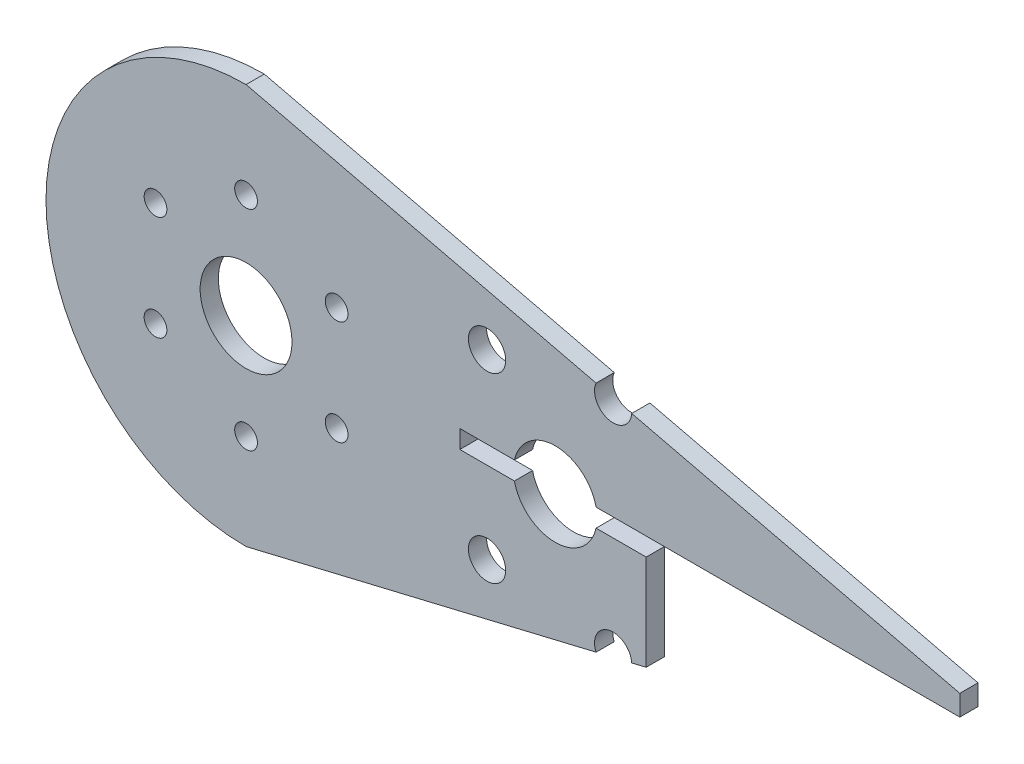
SolidWorks part; units mm, degrees
ref_plane "前视基准面" through (0, 0, 0) normal (0, 0, 1) x (1, 0, 0)
ref_plane "上视基准面" through (0, 0, 0) normal (0, 1, 0) x (1, 0, 0)
ref_plane "右视基准面" through (0, 0, 0) normal (1, 0, 0) x (0, 0, -1)
sketch "草图1" plane through (0, 0, 0) normal (0, 0, 1) x (1, 0, 0)
  line L0 (-38.999, 0) -> (5.001, 0) construction
  line L1 (-38.999, 22.002) -> (5.001, 22.002) construction
  line L6 (-38.999, 22.002) -> (-38.999, -22.002) construction
  line L7 (-38.999, -22.002) -> (5.001, -22.002) construction
  line L11 (5.001, 22.002) -> (5.001, -22.002) construction
  line L12 (5.001, 22.002) -> (5.001, 1) construction
  line L13 (-15.489, 1) -> (-9.489, 1)
  line L31 (-15.489, 1) -> (-15.489, -1)
  line L35 (-15.489, -1) -> (-9.489, -1)
  line L36 (-9.489, 1) -> (-9.489, -1) construction
  line L37 (5.001, 1) -> (-0.509, 1)
  line L39 (5.001, -1) -> (-0.509, -1)
  line L40 (-0.509, 1) -> (-0.509, -1) construction
  line L41 (5.001, -1) -> (5.001, -22.002) construction
  line L44 (5.001, 11.501) -> (5.001, 1) construction
  line L45 (5.001, -1) -> (5.001, -11.501)
  line L46 (5.001, 1) -> (39.4927, 1)
  line L47 (5.001, 11.501) -> (39.4927, 3.2692)
  line L48 (39.4927, 3.2692) -> (39.4927, 1)
  line L49 (-38.999, 22.002) -> (-0.509, 12.816)
  line L50 (3.4077, 11.8813) -> (5.001, 11.501)
  line L51 (-38.999, -22.002) -> (-0.509, -12.816)
  line L52 (3.4077, -11.8813) -> (5.001, -11.501)
  circle A3 centre (-38.999, 0) radius 5.05
  circle A6 centre (-38.999, 0) radius 11.5 construction
  circle A7 centre (-38.999, -11.5) radius 1.25
  circle A18 centre (-38.999, 0) radius 22.002 construction
  arc A35 (-38.999, 22.002) -> (-38.999, -22.002) centre (-38.999, 0) ccw
  circle A37 centre (-4.999, 0) radius 4.6 construction
  arc A38 (-0.509, 1) -> (-9.489, 1) centre (-4.999, 0) ccw
  arc A39 (-0.509, -1) -> (-9.489, -1) centre (-4.999, 0) cw
  circle A43 centre (-12.499, -10) radius 2.05
  circle A45 centre (-38.999, 0) radius 16.5 construction
  circle A47 centre (-48.9583, -5.75) radius 1.25
  circle A48 centre (-12.499, 10) radius 2.05
  circle A49 centre (-48.9583, 5.75) radius 1.25
  circle A50 centre (-38.999, 11.5) radius 1.25
  circle A51 centre (-29.0397, 5.75) radius 1.25
  circle A52 centre (-29.0397, -5.75) radius 1.25
  arc A53 (-0.509, 12.816) -> (3.4077, 11.8813) centre (1.3674, 12.0051) ccw
  arc A54 (-0.509, -12.816) -> (3.4077, -11.8813) centre (1.3674, -12.0051) cw
  point P45 (-61.001, 0)
  dimension "D3" = 10.1
  dimension "D4" = 44
  dimension "D5" = 9.2
  dimension "D6" = 10
  dimension "D7" = 23
  dimension "D8" = 2.5
  dimension "D9" = 2
  dimension "D11" = 33
  dimension "D2" = 44.004
  dimension "D10" = 6
  dimension "D16" = 6
extrude "凸台-拉伸1" add sketch "草图1" along normal blind 2
